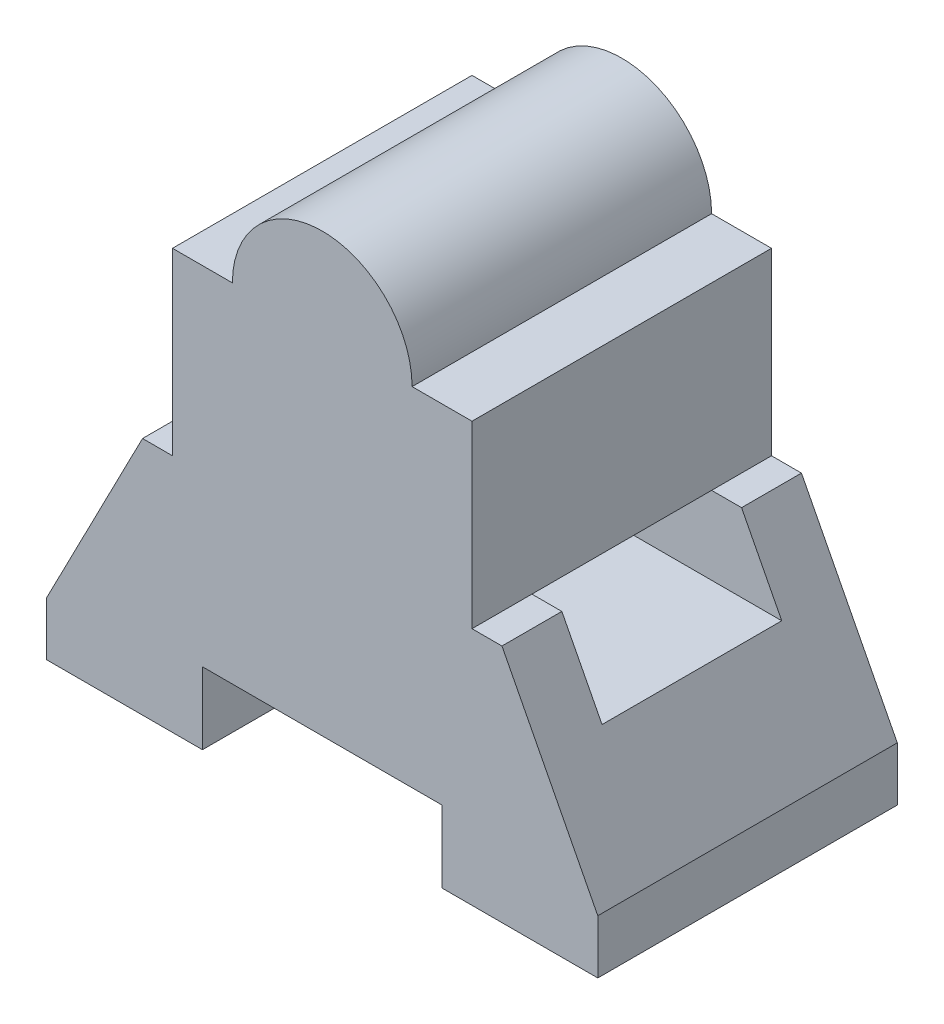
SolidWorks part; units mm, degrees
ref_plane "Front Plane" through (0, 0, 0) normal (0, 0, 1) x (1, 0, 0)
ref_plane "Top Plane" through (0, 0, 0) normal (0, 1, 0) x (1, 0, 0)
ref_plane "Right Plane" through (0, 0, 0) normal (1, 0, 0) x (0, 0, -1)
sketch "Sketch1" plane through (0, 0, 0) normal (0, 0, 1) x (1, 0, 0)
  line L0 (0, 0) -> (26, 0)
  line L1 (92, 0) -> (92, 9)
  line L2 (92, 9) -> (76, 40)
  line L3 (76, 40) -> (71, 40)
  line L4 (71, 40) -> (71, 70)
  line L5 (71, 70) -> (61, 70)
  line L6 (21, 70) -> (21, 40)
  line L7 (21, 40) -> (16, 40)
  line L8 (16, 40) -> (0, 9)
  line L9 (0, 9) -> (0, 0)
  line L10 (31, 70) -> (21, 70)
  line L11 (26, 0) -> (26, 12)
  line L12 (26, 12) -> (66, 12)
  line L13 (66, 12) -> (66, 0)
  line L14 (66, 0) -> (92, 0)
  arc A0 (61, 70) -> (31, 70) centre (46, 70) ccw
  point P9 (73.5, 40)
  dimension "D7" = 15
  dimension "D1" = 92
  dimension "D2" = 9
  dimension "D3" = 40
  dimension "D4" = 60
  dimension "D5" = 70
  dimension "D6" = 50
  dimension "D8" = 12
  dimension "D9" = 40
extrude "Boss-Extrude1" add sketch "Sketch1" along normal blind 50 contours L6 L7 L8 L9 L0 L11 L12 L13 L14 L1 L2 L3 L4 L5 A0 L10
sketch "Sketch5" plane through (0, 0, 0) normal (1, 0, 0) x (0, 0, -1)
  line L0 (-10, 40) -> (-10, 27)
  line L1 (-10, 27) -> (-40, 27)
  line L2 (-40, 27) -> (-40, 40)
  line L3 (-40, 40) -> (-10, 40)
  line L4 (0, 9) -> (0, 40)
  line L5 (-50, 9) -> (0, 9)
  line L6 (-50, 40) -> (-50, 9)
  line L7 (0, 40) -> (-50, 40)
  line L8 (0, 9) -> (0, 40)
  line L9 (-50, 9) -> (0, 9)
  line L10 (-50, 40) -> (-50, 9)
  line L11 (0, 40) -> (-50, 40)
  point P8 (-25, 40)
  dimension "D2" = 13
  dimension "D3" = 30
  dimension "D1" = 0
extrude "Cut-Extrude1" cut sketch "Sketch5" along normal through all contours L3 L2 L1 L0
